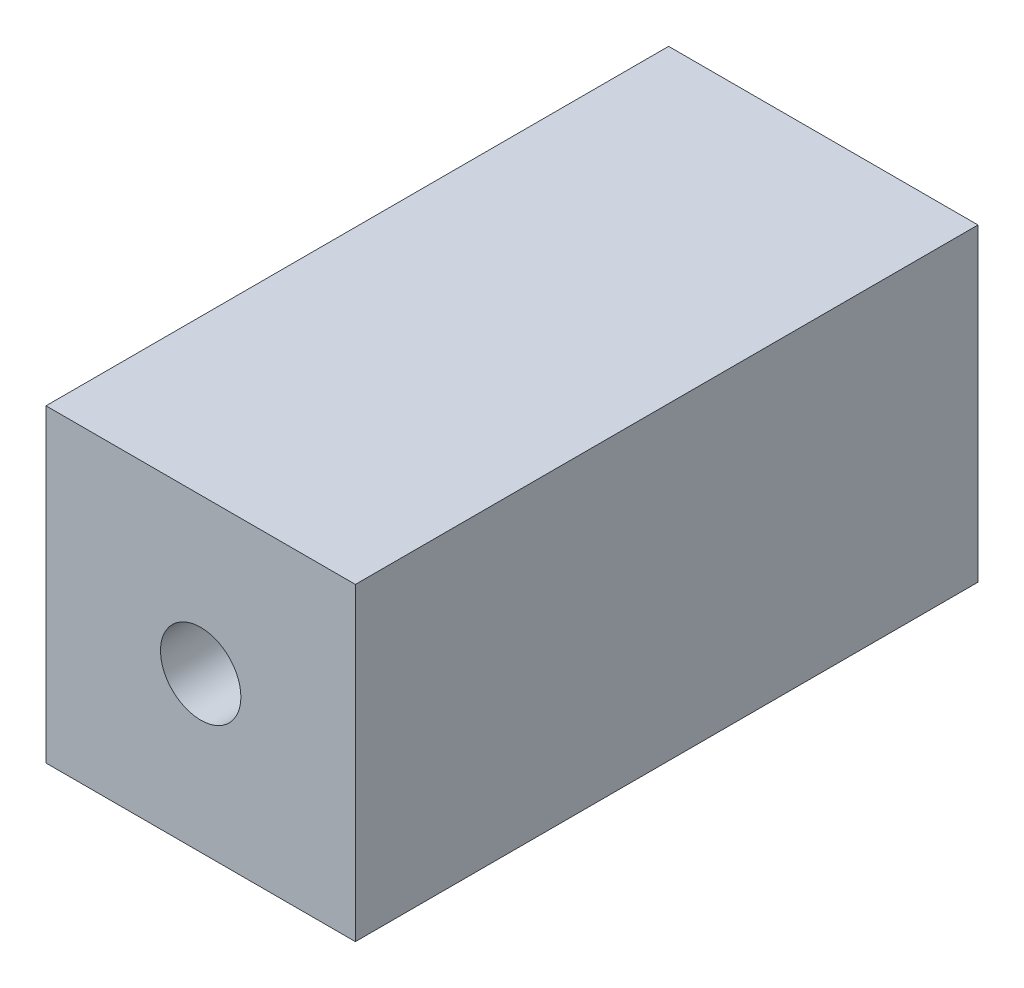
SolidWorks part; units mm, degrees
ref_plane "Front Plane" through (0, 0, 0) normal (0, 0, 1) x (1, 0, 0)
ref_plane "Top Plane" through (0, 0, 0) normal (0, 1, 0) x (1, 0, 0)
ref_plane "Right Plane" through (0, 0, 0) normal (1, 0, 0) x (0, 0, -1)
sketch "Sketch1" plane through (0, 0, 0) normal (0, 0, 1) x (1, 0, 0)
  line L1 (-12.7, -12.7) -> (12.7, -12.7)
  line L2 (-12.7, -12.7) -> (-12.7, 12.7)
  line L3 (-12.7, 12.7) -> (12.7, 12.7)
  line L4 (12.7, -12.7) -> (12.7, 12.7)
  line L5 (-12.7, -12.7) -> (12.7, 12.7) construction
  line L6 (-12.7, 12.7) -> (12.7, -12.7) construction
  point P0 (0, 0)
  dimension "D1" = 25.4
  dimension "D2" = 25.4
extrude "Boss-Extrude1" add sketch "Sketch1" along normal mid plane 51.1156
sketch "Sketch2" plane through (0, 0, 25.5578) normal (0, 0, 1) x (1, 0, 0)
  circle A0 centre (0, 0) radius 3.3
  dimension "D1" = 6.6
extrude "Cut-Extrude1" cut sketch "Sketch2" against normal through all
